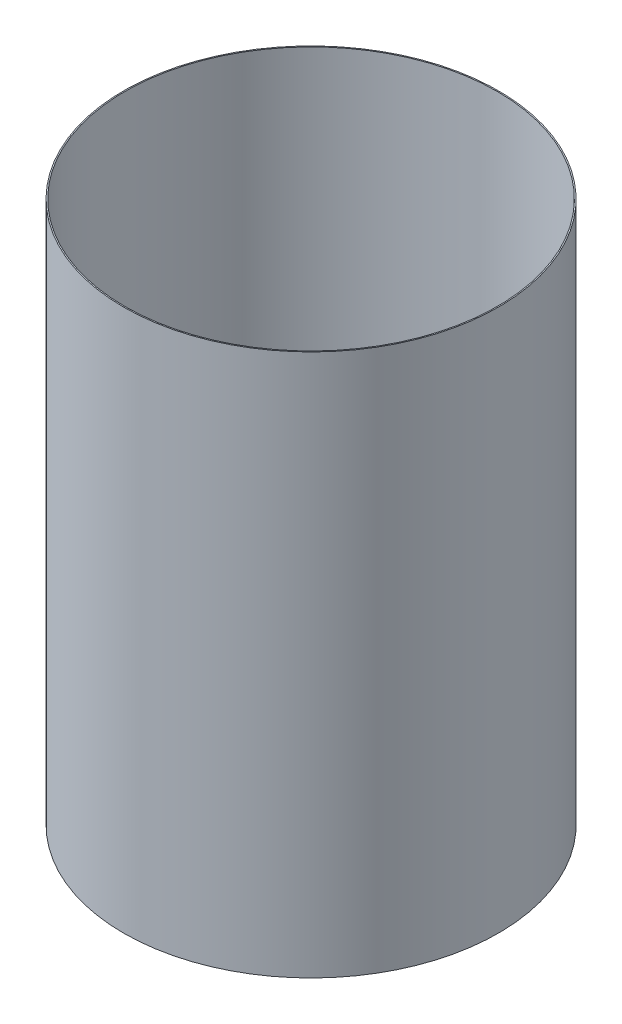
SolidWorks part; units mm, degrees
ref_plane "Front Plane" through (0, 0, 0) normal (0, 0, 1) x (1, 0, 0)
ref_plane "Top Plane" through (0, 0, 0) normal (0, 1, 0) x (1, 0, 0)
ref_plane "Right Plane" through (0, 0, 0) normal (1, 0, 0) x (0, 0, -1)
ref_plane "Plane4" through (0, 0, 0) normal (0, 0, -1) x (-1, 0, 0)
sketch "Sketch1" plane through (0, 0, 0) normal (0, 0, -1) x (-1, 0, 0)
  line L0 (-7.95, 81.5) -> (-7.95, 58.5)
  line L1 (-7.95, 58.5) -> (-7.9, 58.5)
  line L2 (-7.9, 58.5) -> (-7.9, 81.5)
  line L3 (-7.9, 81.5) -> (-7.95, 81.5)
  line L4 (0, 58.5) -> (0, 81.5) construction
  dimension "D1" = 7.9
  dimension "D2" = 7.95
  dimension "D3" = 58.5
  dimension "D4" = 81.5
revolve "Revolve1" add sketch "Sketch1" angle 360 about L4
